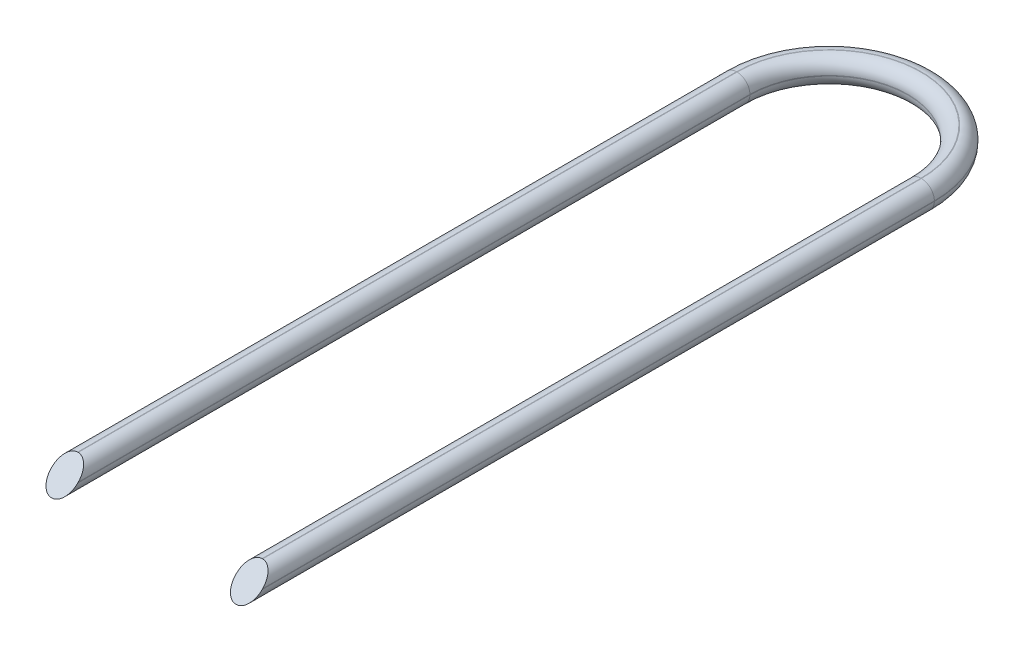
SolidWorks part; units mm, degrees
material "AISI 1020 Сталь, холоднокатаная"
ref_plane "Спереди" through (0, 0, 0) normal (0, 0, 1) x (1, 0, 0)
ref_plane "Сверху" through (0, 0, 0) normal (0, 1, 0) x (1, 0, 0)
ref_plane "Справа" through (0, 0, 0) normal (1, 0, 0) x (0, 0, -1)
sketch "Эскиз1" plane through (0, 0, 0) normal (0, 0, 1) x (1, 0, 0)
  line L1 (-19.1037, 0.4918) -> (-19.0037, 0.4918)
  line L2 (-21.5537, -1.9582) -> (-21.5537, -2.0582)
  line L3 (-19.1037, -4.5082) -> (-19.0037, -4.5082)
  line L4 (-16.5537, -1.9582) -> (-16.5537, -2.0582)
  line L5 (-21.5537, 0.4918) -> (-16.5537, -4.5082) construction
  line L6 (-21.5537, -4.5082) -> (-16.5537, 0.4918) construction
  arc A1 (-21.5537, -2.0582) -> (-19.1037, -4.5082) centre (-19.1037, -2.0582) ccw
  arc A2 (-19.0037, -4.5082) -> (-16.5537, -2.0582) centre (-19.0037, -2.0582) ccw
  arc A3 (-16.5537, -1.9582) -> (-19.0037, 0.4918) centre (-19.0037, -1.9582) ccw
  arc A4 (-21.5537, -1.9582) -> (-19.1037, 0.4918) centre (-19.1037, -1.9582) cw
  dimension "D1" = 2.45
  dimension "D2" = 5
  dimension "D3" = 5
sketch "Эскиз2" plane through (0, 0, 0) normal (0, 1, 0) x (1, 0, 0)
  line L0 (-19.0537, 0) -> (-19.0537, 130)
  line L1 (-21.5537, 0) -> (-16.5537, 0) construction
  line L2 (-1.5537, 0) -> (-1.5537, 6.7275) construction
  line L3 (15.9463, 0) -> (15.9463, 130)
  arc A0 (15.9463, 130) -> (-19.0537, 130) centre (-1.5537, 130) ccw
  dimension "D3" = 0
  dimension "D1" = 130
  dimension "D2" = 17.5
sweep "По траектории1" add profiles "Эскиз1" path "Эскиз2"
sketch "Эскиз3" plane through (-21.5537, 0, 0) normal (-1, 0, 0) x (0, 0, 1)
  line L0 (0, 0.4918) -> (-5, 0.4918)
  line L1 (0, 0.4918) -> (-130, 0.4918) construction
  line L2 (-5, 0.4918) -> (0, -4.5082)
  line L3 (0, -4.5082) -> (0, 0.4918)
  dimension "D1" = 5
extrude "Вырез-Вытянуть1" cut sketch "Эскиз3" against normal through all
